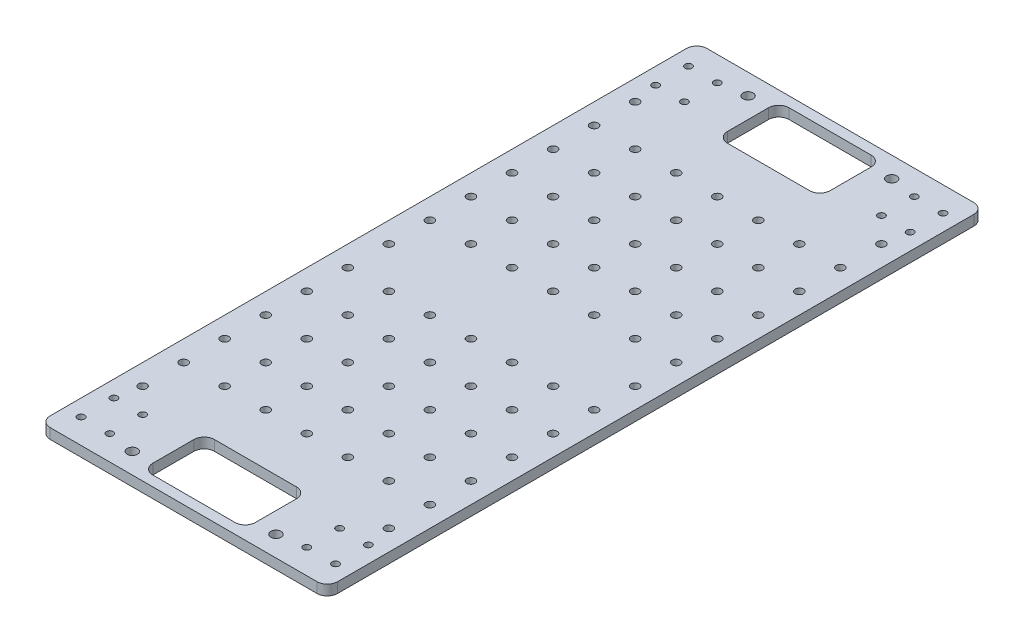
SolidWorks part; units mm, degrees
ref_plane "前视基准面" through (0, 0, 0) normal (0, 0, 1) x (1, 0, 0)
ref_plane "上视基准面" through (0, 0, 0) normal (0, 1, 0) x (1, 0, 0)
ref_plane "右视基准面" through (0, 0, 0) normal (1, 0, 0) x (0, 0, -1)
other "Configuration Table"
sketch "草图1" plane through (0, 0, 0) normal (0, 1, 0) x (1, 0, 0)
  line L0 (0, 160) -> (0, -49840) construction
  line L5 (-100, -160) -> (100, 160) construction
  line L6 (-100, 160) -> (100, -160) construction
  line L7 (-100, 160) -> (-70, 160)
  line L11 (-1000, 0) -> (49000, 0) construction
  line L12 (-70, 160) -> (-70, 153)
  line L13 (-70, 153) -> (-70, 127)
  line L14 (-70, 127) -> (-70, 120)
  line L15 (-70, 153) -> (-40, 153)
  line L16 (-40, 153) -> (-40, 127)
  line L17 (-40, 127) -> (-70, 127)
  line L18 (-70, 153) -> (-70, 148)
  line L19 (-70, 127) -> (-70, 132)
  line L20 (-40, 127) -> (-48, 127)
  line L21 (-48, 127) -> (-48, 132)
  line L22 (-48, 132) -> (-40, 132)
  line L23 (-70, 132) -> (-62, 132)
  line L24 (-62, 132) -> (-62, 127)
  line L25 (-5, 125) -> (5, 125)
  line L26 (-145.3082, 0) -> (-135.3082, 0)
  line L27 (-70, 0) -> (-60, 0)
  line L28 (-70, 120) -> (0, 120)
  line L29 (-20, -125) -> (20, -125)
  line L30 (70, 155) -> (70, 120)
  line L31 (-20, 155) -> (20, 155)
  line L32 (70, -155) -> (70, -120)
  line L33 (-70, -155) -> (-70, -120)
  line L34 (-25, 150) -> (-25, 130)
  line L35 (-25, -130) -> (-25, -150)
  line L36 (0, 140) -> (-25, 140)
  line L37 (-25, 140) -> (-25, 155)
  line L38 (-25, 140) -> (-25, 125)
  line L39 (-20, 125) -> (-5, 125)
  line L43 (25, 140) -> (25, 130)
  line L44 (20, 125) -> (5, 125)
  line L46 (25, 140) -> (25, 150)
  line L47 (25, -125) -> (5, -125)
  line L48 (25, -140) -> (25, -130)
  line L49 (25, -140) -> (25, -150)
  line L50 (20, -155) -> (5, -155)
  line L51 (5, -155) -> (5, -125)
  line L52 (-25, -140) -> (-25, -155)
  line L53 (-25, -140) -> (-25, -125)
  line L54 (-25, -125) -> (-5, -125)
  line L55 (-5, -155) -> (-5, -125)
  line L56 (-20, -155) -> (-5, -155)
  line L57 (-25, -155) -> (25, -155)
  line L58 (25, -125) -> (25, -155)
  line L59 (60, 20) -> (70, 20)
  line L62 (-65, 160) -> (65, 160)
  line L63 (-70, 160) -> (-70, -160)
  line L64 (-65, -160) -> (65, -160)
  line L65 (70, 160) -> (70, -160)
  circle A8 centre (62, -148) radius 1.7
  circle A9 centre (62, -132) radius 1.7
  circle A10 centre (48, -132) radius 1.7
  circle A11 centre (48, -148) radius 1.7
  circle A12 centre (-48, -132) radius 1.7
  circle A13 centre (-62, -132) radius 1.7
  circle A14 centre (-48, -148) radius 1.7
  circle A15 centre (-62, -148) radius 1.7
  circle A23 centre (35, 150) radius 2.5
  circle A24 centre (-135.3082, 0) radius 2
  circle A25 centre (-135.3082, 20) radius 2
  circle A26 centre (-135.3082, 40) radius 2
  circle A27 centre (-135.3082, 60) radius 2
  circle A28 centre (-135.3082, 80) radius 2
  circle A29 centre (-135.3082, 100) radius 2
  circle A30 centre (-135.3082, 120) radius 2
  circle A31 centre (-35, 150) radius 2.5
  circle A36 centre (-60, 0) radius 2
  circle A37 centre (-60, 20) radius 2
  circle A38 centre (-60, 40) radius 2
  circle A39 centre (-60, 60) radius 2
  circle A40 centre (-60, 80) radius 2
  circle A41 centre (-60, 100) radius 2
  circle A42 centre (-60, 120) radius 2
  circle A43 centre (-40, 20) radius 2
  circle A44 centre (-40, 40) radius 2
  circle A45 centre (-40, 60) radius 2
  circle A46 centre (-40, 80) radius 2
  circle A47 centre (-40, 100) radius 2
  circle A48 centre (-20, 20) radius 2
  circle A49 centre (-20, 40) radius 2
  circle A50 centre (-20, 60) radius 2
  circle A51 centre (-20, 80) radius 2
  circle A52 centre (-20, 100) radius 2
  circle A53 centre (0, 20) radius 2
  circle A54 centre (0, 40) radius 2
  circle A55 centre (0, 60) radius 2
  circle A56 centre (0, 80) radius 2
  circle A57 centre (0, 100) radius 2
  circle A58 centre (20, 20) radius 2
  circle A59 centre (20, 40) radius 2
  circle A60 centre (20, 60) radius 2
  circle A61 centre (20, 80) radius 2
  circle A62 centre (20, 100) radius 2
  circle A63 centre (40, 20) radius 2
  circle A64 centre (40, 40) radius 2
  circle A65 centre (40, 60) radius 2
  circle A66 centre (40, 80) radius 2
  circle A67 centre (40, 100) radius 2
  circle A68 centre (60, 20) radius 2
  circle A69 centre (60, 40) radius 2
  circle A70 centre (60, 60) radius 2
  circle A71 centre (60, 80) radius 2
  circle A72 centre (60, 100) radius 2
  circle A73 centre (60, 0) radius 2
  circle A74 centre (60, 120) radius 2
  circle A75 centre (60, -100) radius 2
  circle A76 centre (60, -80) radius 2
  circle A77 centre (60, -60) radius 2
  circle A78 centre (60, -40) radius 2
  circle A79 centre (60, -20) radius 2
  circle A80 centre (40, -100) radius 2
  circle A81 centre (40, -80) radius 2
  circle A82 centre (40, -60) radius 2
  circle A83 centre (40, -40) radius 2
  circle A84 centre (40, -20) radius 2
  circle A85 centre (20, -100) radius 2
  circle A86 centre (20, -80) radius 2
  circle A87 centre (20, -60) radius 2
  circle A88 centre (20, -40) radius 2
  circle A89 centre (20, -20) radius 2
  circle A90 centre (0, -100) radius 2
  circle A91 centre (0, -80) radius 2
  circle A92 centre (0, -60) radius 2
  circle A93 centre (0, -40) radius 2
  circle A94 centre (0, -20) radius 2
  circle A95 centre (-20, -100) radius 2
  circle A96 centre (-20, -80) radius 2
  circle A97 centre (-20, -60) radius 2
  circle A98 centre (-20, -40) radius 2
  circle A99 centre (-20, -20) radius 2
  circle A100 centre (-40, -100) radius 2
  circle A101 centre (-40, -80) radius 2
  circle A102 centre (-40, -60) radius 2
  circle A103 centre (-40, -40) radius 2
  circle A104 centre (-40, -20) radius 2
  circle A105 centre (-60, -100) radius 2
  circle A106 centre (-60, -80) radius 2
  circle A107 centre (-60, -60) radius 2
  circle A108 centre (-60, -40) radius 2
  circle A109 centre (-60, -20) radius 2
  circle A110 centre (60, -120) radius 2
  circle A111 centre (-60, -120) radius 2
  circle A112 centre (35, -150) radius 2.5
  circle A113 centre (-35, -150) radius 2.5
  arc A114 (65, -160) -> (70, -155) centre (65, -155) ccw
  arc A115 (20, -155) -> (25, -150) centre (20, -150) ccw
  arc A116 (25, -130) -> (20, -125) centre (20, -130) ccw
  arc A117 (-25, -130) -> (-20, -125) centre (-20, -130) cw
  arc A118 (-25, -150) -> (-20, -155) centre (-20, -150) ccw
  arc A119 (-70, -155) -> (-65, -160) centre (-65, -155) ccw
  arc A120 (65, 160) -> (70, 155) centre (65, 155) cw
  arc A121 (20, 155) -> (25, 150) centre (20, 150) cw
  arc A122 (25, 130) -> (20, 125) centre (20, 130) cw
  arc A123 (-20, 125) -> (-25, 130) centre (-20, 130) cw
  arc A124 (-25, 150) -> (-20, 155) centre (-20, 150) cw
  arc A125 (-70, 155) -> (-65, 160) centre (-65, 155) cw
  circle A126 centre (-62, 148) radius 1.7
  circle A127 centre (-48, 148) radius 1.7
  circle A128 centre (-62, 132) radius 1.7
  circle A129 centre (-48, 132) radius 1.7
  circle A130 centre (62, 132) radius 1.7
  circle A131 centre (48, 132) radius 1.7
  circle A132 centre (48, 148) radius 1.7
  circle A133 centre (62, 148) radius 1.7
  point P0 (0, 0)
  dimension "D19" = 7
  dimension "D23" = 10
  dimension "D18" = 4
  dimension "D21" = 4
  dimension "D24" = 5
  dimension "D1" = 200
  dimension "D2" = 320
  dimension "D3" = 10
  dimension "D5" = 7
  dimension "D7" = 30
  dimension "D8" = 5
  dimension "D14" = 25
  dimension "D15" = 15
  dimension "D16" = 15
  dimension "D17" = 20
  dimension "D22" = 7
  dimension "D20" = 10
extrude "凸台-拉伸2" add sketch "草图1" along normal blind 5
